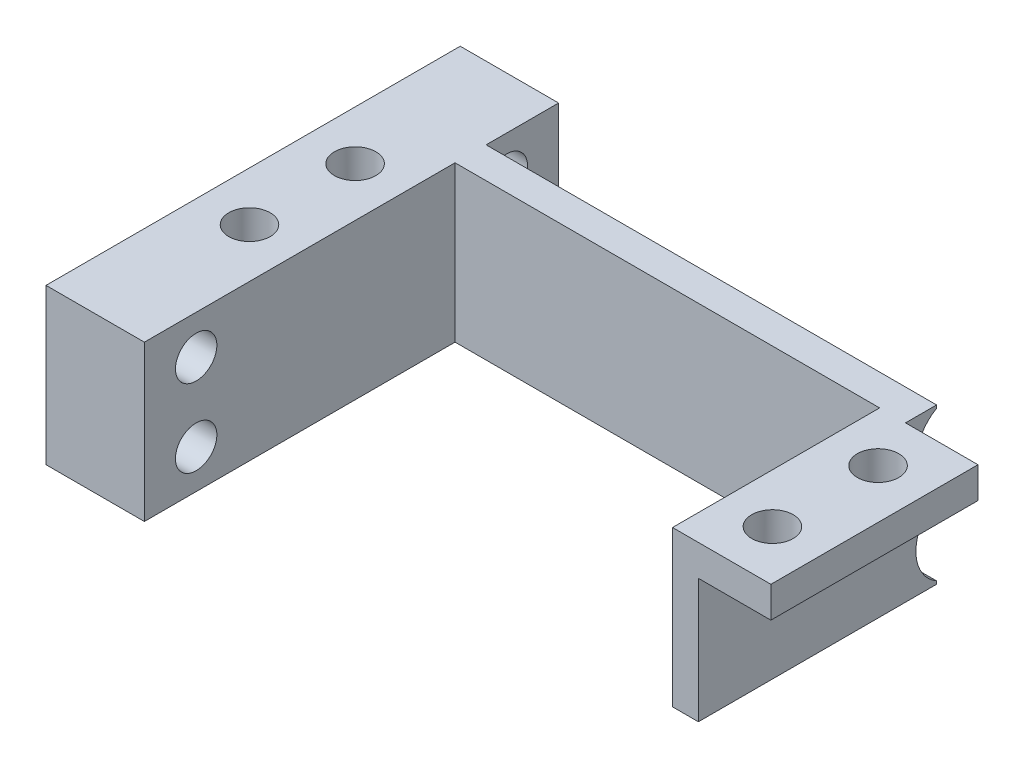
SolidWorks part; units mm, degrees
ref_plane "Front Plane" through (0, 0, 0) normal (0, 0, 1) x (1, 0, 0)
ref_plane "Top Plane" through (0, 0, 0) normal (0, 1, 0) x (1, 0, 0)
ref_plane "Right Plane" through (0, 0, 0) normal (1, 0, 0) x (0, 0, -1)
sketch "Sketch1" plane through (0, 0, 0) normal (0, 0, 1) x (1, 0, 0)
  line L1 (0, 0) -> (46, 0)
  line L2 (0, 0) -> (0, 15)
  line L3 (0, 15) -> (46, 15)
  line L4 (46, 0) -> (46, 15)
  dimension "D1" = 46
  dimension "D2" = 15
extrude "Boss-Extrude1" add sketch "Sketch1" along normal blind 3
sketch "Sketch3" plane through (0, 0, 3) normal (0, 0, 1) x (1, 0, 0)
  line L1 (0, 0) -> (2.5, 0)
  line L2 (0, 0) -> (0, 15)
  line L3 (0, 15) -> (2.5, 15)
  line L4 (2.5, 0) -> (2.5, 15)
  dimension "D1" = 15
  dimension "D2" = 2.5
extrude "Boss-Extrude2" add sketch "Sketch3" along normal blind 20
sketch "Sketch4" plane through (0, 0, 0) normal (-1, 0, 0) x (0, 0, 1)
  line L1 (23, 15) -> (3, 15)
  line L2 (23, 15) -> (23, 12)
  line L3 (23, 12) -> (3, 12)
  line L4 (3, 15) -> (3, 12)
  dimension "D1" = 3
  dimension "D2" = 20
extrude "Boss-Extrude3" add sketch "Sketch4" along normal blind 7
sketch "Sketch5" plane through (0, 15, 0) normal (0, 1, 0) x (1, 0, 0)
  line L0 (0, -3) -> (0, -23) construction
  line L1 (-2.25, -23) -> (-2.25, -20.35) construction
  line L2 (2.5, -23) -> (-7, -23) construction
  line L3 (-2.25, -23) -> (0, -23) construction
  line L4 (-7, -13) -> (2.5, -13) construction
  line L5 (-7, -23) -> (-7, -3) construction
  line L6 (2.5, -23) -> (2.5, -3) construction
  circle A0 centre (-2.25, -18.1) radius 2.25 construction
  circle A1 centre (-2.25, -18.1) radius 2
  circle A2 centre (-2.25, -7.9) radius 2
  dimension "D2" = 4.5
  dimension "D4" = 4
  dimension "D1" = 2.65
  dimension "D3" = 2.25
extrude "Cut-Extrude1" cut sketch "Sketch5" against normal blind 7
ref_plane "Plane1" through (23, 0, 0) normal (1, 0, 0) x (0, 0, -1)
mirror "Mirror1" about plane through (23, 0, 0) normal (1, 0, 0) of "Boss-Extrude2", "Boss-Extrude3", "Cut-Extrude1"
ref_plane "Plane2" through (-7, 12, 23) normal (0, 1, 0) x (1, 0, 0)
ref_plane "Plane3" through (0, 0, 13) normal (0, 0, 1) x (1, 0, 0)
sketch "Sketch7" plane through (0, 0, 23) normal (0, 0, 1) x (1, 0, 0)
  line L1 (2.5, 15) -> (-7, 15)
  line L2 (2.5, 15) -> (2.5, 0)
  line L3 (2.5, 0) -> (-7, 0)
  line L4 (-7, 15) -> (-7, 0)
  dimension "D1" = 9.5
extrude "Boss-Extrude4" add sketch "Sketch7" along normal blind 10
sketch "Sketch8" plane through (-7, 0, 0) normal (-1, 0, 0) x (0, 0, 1)
  line L0 (28, 0) -> (28, 15) construction
  line L1 (33, 0) -> (23, 0) construction
  line L2 (33, 15) -> (3, 15) construction
  line L3 (33, 7.5) -> (23, 7.5) construction
  line L4 (33, 15) -> (33, 0) construction
  line L5 (23, 12) -> (23, 0) construction
  circle A0 centre (28, 11.25) radius 2
  circle A1 centre (28, 3.75) radius 2
  dimension "D1" = 4
  dimension "D2" = 3.75
extrude "Cut-Extrude2" cut sketch "Sketch8" against normal blind 10
mirror "Mirror4" about plane through (0, 0, 13) normal (0, 0, 1) of "Cut-Extrude2", "Boss-Extrude4"
sketch "Sketch9" plane through (2.5, 0, 0) normal (1, 0, 0) x (0, 0, -1)
  arc A0 (0.6081, 7.5) -> (3.3919, 7.5) centre (2, 3.75) ccw
  arc A1 (3.3919, 7.5) -> (0.6081, 7.5) centre (2, 11.25) ccw
  dimension "D1" = 8
  dimension "D2" = 8
extrude "Cut-Extrude3" cut sketch "Sketch9" along normal up to next
